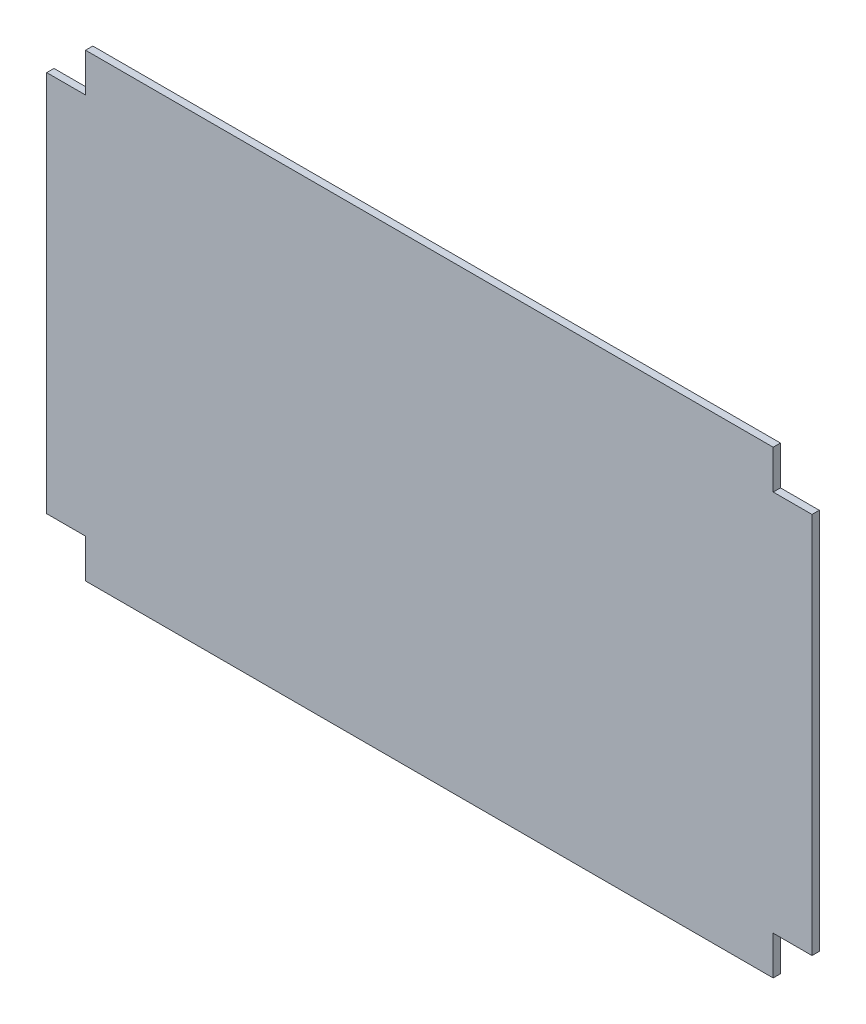
SolidWorks part; units mm, degrees
ref_plane "前基準面" through (0, 0, 0) normal (0, 0, 1) x (1, 0, 0)
ref_plane "上基準面" through (0, 0, 0) normal (0, 1, 0) x (1, 0, 0)
ref_plane "右基準面" through (0, 0, 0) normal (1, 0, 0) x (0, 0, -1)
sketch "草圖1" plane through (0, 0, 0) normal (0, 0, 1) x (1, 0, 0)
  line L1 (-250.4, 150.4) -> (250.4, 150.4)
  line L2 (-250.4, 150.4) -> (-250.4, -150.4)
  line L3 (-250.4, -150.4) -> (250.4, -150.4)
  line L4 (250.4, 150.4) -> (250.4, -150.4)
  line L5 (-250.4, 150.4) -> (250.4, -150.4) construction
  line L6 (-250.4, -150.4) -> (250.4, 150.4) construction
  point P0 (0, 0)
  dimension "D1" = 500.8
  dimension "D2" = 300.8
extrude "填料-伸長1" add sketch "草圖1" along normal blind 4.75 contours L1 L4 L3 L2
sketch "草圖2" plane through (0, 0, 0) normal (0, 0, -1) x (-1, 0, 0)
  line L1 (-250.4, 150.4) -> (-225, 150.4)
  line L2 (-250.4, 150.4) -> (-250.4, 125)
  line L3 (-250.4, 125) -> (-225, 125)
  line L4 (-225, 150.4) -> (-225, 125)
  line L5 (-250.4, -150.4) -> (-225, -150.4)
  line L6 (-250.4, -150.4) -> (-250.4, -125)
  line L7 (-250.4, -125) -> (-225, -125)
  line L8 (-225, -150.4) -> (-225, -125)
  line L9 (250.4, 150.4) -> (225, 150.4)
  line L10 (250.4, 150.4) -> (250.4, 125)
  line L11 (250.4, 125) -> (225, 125)
  line L12 (225, 150.4) -> (225, 125)
  line L13 (250.4, -150.4) -> (225, -150.4)
  line L14 (250.4, -150.4) -> (250.4, -125)
  line L15 (250.4, -125) -> (225, -125)
  line L16 (225, -150.4) -> (225, -125)
  dimension "D1" = 25.4
  dimension "D2" = 25.4
  dimension "D3" = 25.4
  dimension "D4" = 25.4
  dimension "D5" = 25.4
  dimension "D6" = 25.4
  dimension "D7" = 25.4
  dimension "D8" = 25.4
extrude "除料-伸長1" cut sketch "草圖2" against normal blind 10
